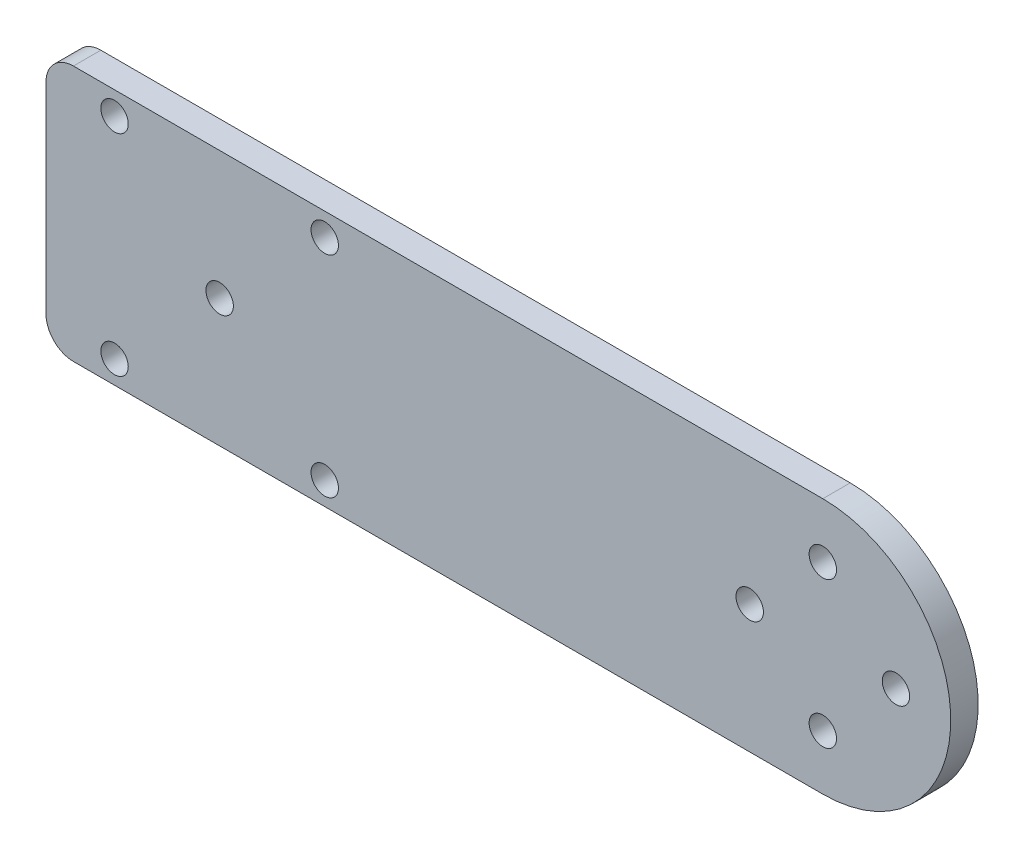
SolidWorks part; units mm, degrees
ref_plane "前视基准面" through (0, 0, 0) normal (0, 0, 1) x (1, 0, 0)
ref_plane "上视基准面" through (0, 0, 0) normal (0, 1, 0) x (1, 0, 0)
ref_plane "右视基准面" through (0, 0, 0) normal (1, 0, 0) x (0, 0, -1)
sketch "草图1" plane through (0, 0, 0) normal (0, 0, 1) x (1, 0, 0)
  line L0 (0, 14) -> (0, -14)
  line L1 (0, 14) -> (-80, 14)
  line L2 (0, -14) -> (-80, -14)
  line L3 (-80, 14) -> (-80, -14)
  line L4 (0, 0) -> (20.2304, 0) construction
  line L5 (-80, 0) -> (-52, 0)
  line L6 (-80, 14) -> (-52, 14)
  line L7 (-80, 14) -> (-80, -14)
  line L8 (-80, -14) -> (-52, -14)
  line L9 (-52, 14) -> (-52, -14)
  line L10 (-80, 14) -> (-52, -14)
  line L11 (-52, 14) -> (-80, -14)
  line L13 (-80, 14) -> (-85, 14)
  line L14 (-80, 14) -> (-80, -14)
  line L15 (-80, -14) -> (-85, -14)
  line L16 (-85, 14) -> (-85, -14)
  circle A0 centre (0, 0) radius 14
  circle A1 centre (0, 0) radius 8
  circle A2 centre (0, 8) radius 1.5
  circle A3 centre (-8, 0) radius 1.5
  circle A4 centre (8, 0) radius 1.5
  circle A5 centre (0, -8) radius 1.5
  circle A6 centre (-77.5, 11.5) radius 1.5
  circle A7 centre (-54.5, 11.5) radius 1.5
  circle A8 centre (-77.5, -11.5) radius 1.5
  circle A9 centre (-54.5, -11.5) radius 1.5
  circle A10 centre (-66, 0) radius 1.5
  dimension "D1" = 28
  dimension "D3" = 16
  dimension "D4" = 3
  dimension "D8" = 3
  dimension "D2" = 80
  dimension "D5" = 28
  dimension "D6" = 23
  dimension "D7" = 5
extrude "凸台-拉伸1" add sketch "草图1" along normal blind 3 contours A10 L10 A6 L3 L5 | A10 L5 L3 L11 A8 | A10 L11 A8 L2 L10 A9 | A10 L10 A9 L9 L5 | A10 L5 L9 L11 A7 | A10 L11 A7 L1 L10 A6 | L9 L4 A0 L1 | L4 L9 L2 A0 | A0 L4 A3 A1 A2 L0 | L4 A0 L0 A5 A1 A3 | A4 L4 A0 L0 A2 A1 | L0 L4 A4 A1 A2 | A3 L4 L0 A2 A1 | L4 A3 A1 A5 L0 | L4 L0 A5 A1 A4 | L4 A4 A1 A5 L0 A0 | L14 L13 L16 L15
fillet "圆角1" radius 3 2 edges at (-85, -14, 1.5) (-85, 14, 1.5)
